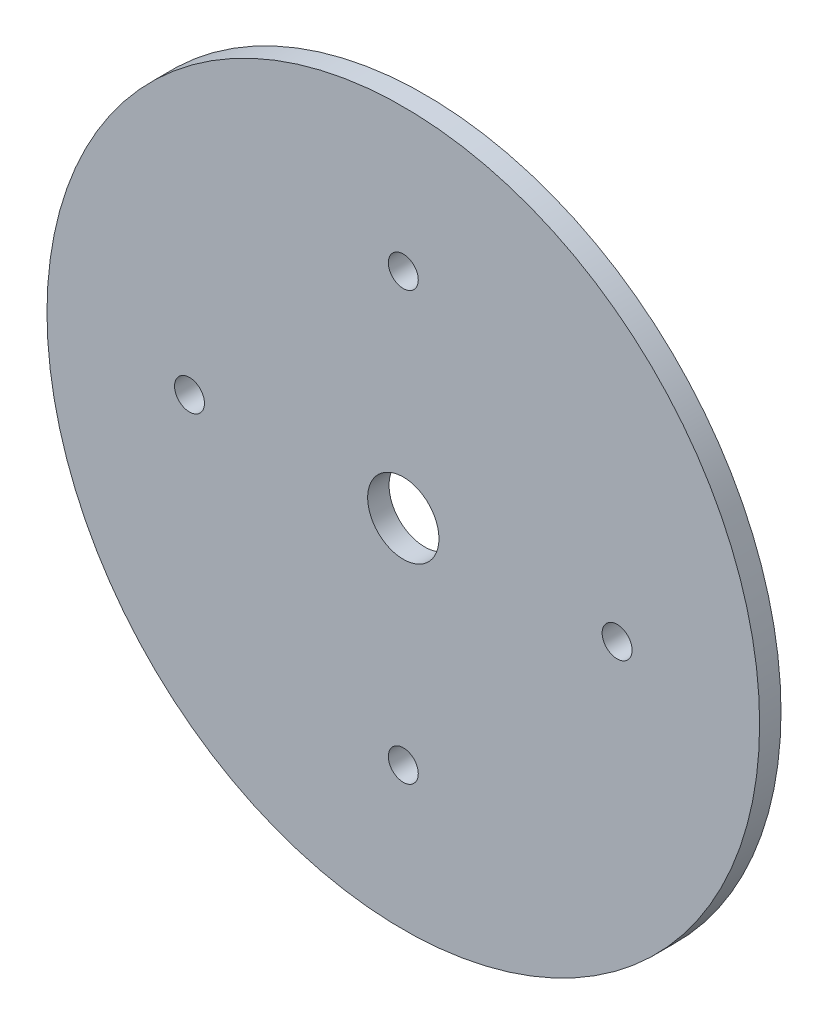
SolidWorks part; units mm, degrees
ref_plane "Front Plane" through (0, 0, 0) normal (0, 0, 1) x (1, 0, 0)
ref_plane "Top Plane" through (0, 0, 0) normal (0, 1, 0) x (1, 0, 0)
ref_plane "Right Plane" through (0, 0, 0) normal (1, 0, 0) x (0, 0, -1)
sketch "Sketch1" plane through (0, 0, 0) normal (0, 0, 1) x (1, 0, 0)
  circle A1 centre (0, 0) radius 50
  circle A7 centre (0, 0) radius 5
  circle A8 centre (0, -30) radius 2.1
  circle A9 centre (-30, 0) radius 2.1
  circle A10 centre (0, 30) radius 2.1
  circle A11 centre (30, 0) radius 2.1
extrude "Boss-Extrude1" add sketch "Sketch1" along normal blind 3
